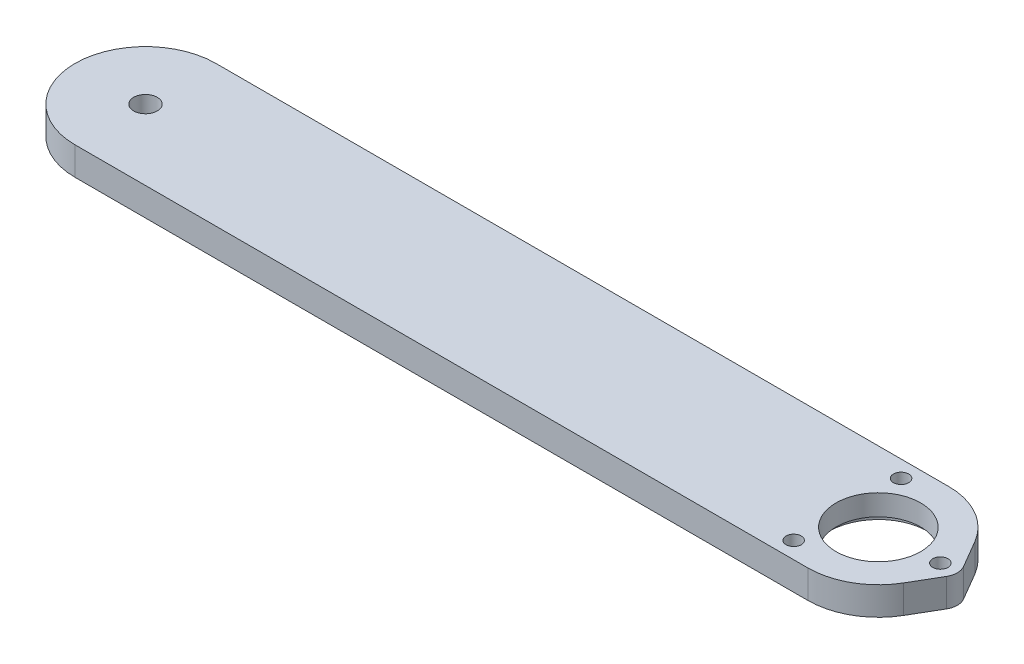
SolidWorks part; units mm, degrees
ref_plane "前视基准面" through (0, 0, 0) normal (0, 0, 1) x (1, 0, 0)
ref_plane "上视基准面" through (0, 0, 0) normal (0, 1, 0) x (1, 0, 0)
ref_plane "右视基准面" through (0, 0, 0) normal (1, 0, 0) x (0, 0, -1)
sketch "草图1" plane through (0, 0, 0) normal (0, 1, 0) x (1, 0, 0)
  line L0 (-65, 0) -> (65, 0) construction
  line L1 (-65, 12.5) -> (65, 12.5)
  line L2 (-65, -12.5) -> (65, -12.5)
  arc A0 (-65, 12.5) -> (-65, -12.5) centre (-65, 0) ccw
  arc A1 (65, -12.5) -> (65, 12.5) centre (65, 0) ccw
  point P2 (0, 0)
  dimension "D2" = 12.5
  dimension "D1" = 130
extrude "凸台-拉伸1" add sketch "草图1" along normal blind 5
sketch "草图10" plane through (0, 0, 0) normal (0, -1, 0) x (1, 0, 0)
  line L0 (75.7955, -6.3014) -> (78.5909, -1.5123)
  line L3 (75.7955, 6.3014) -> (78.5909, 1.5123)
  line L4 (75.7955, -6.3014) -> (75.7955, 6.3014)
  line L5 (76, 0) -> (77.5, 0) construction
  circle A5 centre (76, 0) radius 3 construction
  arc A6 (65, -12.5) -> (65, 12.5) centre (65, 0) ccw construction
  arc A7 (78.5909, -1.5123) -> (78.5909, 1.5123) centre (76, 0) ccw
  dimension "D1" = 6
  dimension "D2" = 1.5
extrude "凸台-拉伸5" add sketch "草图10" against normal up to surface (5 mm away) up to face at (0, 5, 0)
sketch "草图7" plane through (0, 5, 0) normal (0, 1, 0) x (1, 0, 0)
  circle A0 centre (65, 0) radius 7.5
  dimension "D1" = 15
extrude "切除-拉伸2" cut sketch "草图7" against normal up to next
sketch "草图8" plane through (0, 0, 0) normal (0, 1, 0) x (1, 0, 0)
  circle A0 centre (65, 0) radius 8.75
  dimension "D1" = 17.5
extrude "切除-拉伸3" cut sketch "草图8" along normal blind 1.3
sketch "草图9" plane through (0, 0, 0) normal (0, -1, 0) x (1, 0, 0)
  line L0 (65, 0) -> (54, 0) construction
  line L1 (65, 0) -> (59.5, 9.5263) construction
  circle A0 centre (65, 0) radius 11 construction
  circle A5 centre (59.5, 9.5263) radius 1.35
  circle A9 centre (76, 0) radius 1.35
  circle A10 centre (59.5, -9.5263) radius 1.35
  point P12 (65, 0)
  point P15 (65, 0)
  dimension "22" = 22
  dimension "D3" = 2.7
  dimension "D2" = 60
  dimension "D1" = 3
extrude "切除-拉伸4" cut sketch "草图9" against normal up to next
sketch "草图12" plane through (0, 5, 0) normal (0, 1, 0) x (1, 0, 0)
  circle A0 centre (-65, 0) radius 2.1
  dimension "D1" = 4.2
extrude "切除-拉伸5" cut sketch "草图12" against normal up to next
sketch "草图13" plane through (0, 5, 0) normal (0, 1, 0) x (1, 0, 0)
  line L0 (-45, 0) -> (45, 0) construction
  line L1 (-45, 8) -> (45, 8)
  line L2 (-45, -8) -> (45, -8)
  arc A0 (-45, 8) -> (-45, -8) centre (-45, 0) ccw
  arc A1 (45, -8) -> (45, 8) centre (45, 0) ccw
  point P2 (0, 0)
  dimension "D1" = 8
  dimension "D2" = 90
extrude "切除-拉伸6" [suppressed] cut sketch "草图13" against normal up to next
sketch "草图14" [suppressed] plane through (0, 5, 0) normal (0, 1, 0) x (1, 0, 0)
  line L5 (-45, -8) -> (45, -8) construction
  line L6 (45, 8) -> (-45, 8) construction
  line L7 (0, -8) -> (9.2376, 8)
  line L8 (9.2376, 8) -> (13.2376, 8)
  line L9 (13.2376, 8) -> (4, -8)
  line L10 (4, -8) -> (0, -8)
  dimension "D1" = 4
  dimension "D2" = 60
extrude "凸台-拉伸6" [suppressed] add sketch "草图14" against normal up to surface (5 mm away)
pattern_linear "阵列(线性)1" [suppressed] count 3 spacing 25 count 2 spacing 25
mirror "镜向1" [suppressed] about plane through (0, 0, 0) normal (1, 0, 0)
